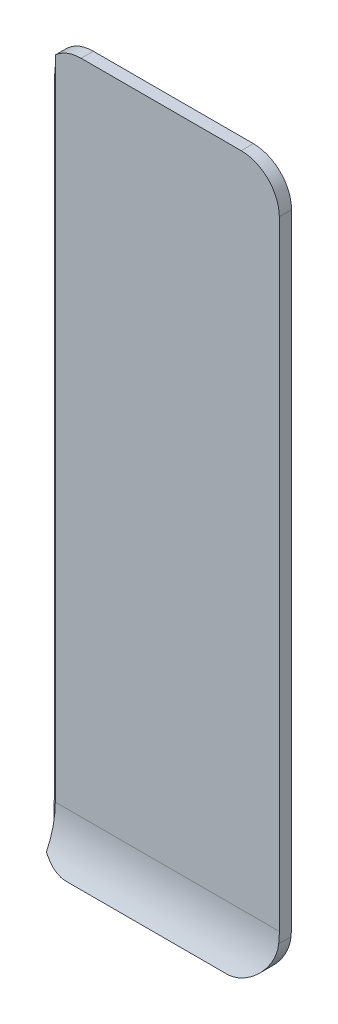
SolidWorks part; units mm, degrees
ref_plane "Front Plane" through (0, 0, 0) normal (0, 0, 1) x (1, 0, 0)
ref_plane "Top Plane" through (0, 0, 0) normal (0, 1, 0) x (1, 0, 0)
ref_plane "Right Plane" through (0, 0, 0) normal (1, 0, 0) x (0, 0, -1)
sketch "Sketch1" plane through (0, 0, 0) normal (0, 0, 1) x (1, 0, 0)
  line L1 (100, 0) -> (519, 0)
  line L2 (0, 100) -> (0, 1748)
  line L3 (100, 1848) -> (519, 1848)
  line L4 (619, 100) -> (619, 1748)
  arc A0 (100, 0) -> (0, 100) centre (100, 100) cw
  arc A1 (519, 0) -> (619, 100) centre (519, 100) ccw
  arc A2 (519, 1848) -> (619, 1748) centre (519, 1748) cw
  arc A3 (0, 1748) -> (100, 1848) centre (100, 1748) cw
  point P8 (0, 0)
  point P11 (619, 0)
  point P14 (619, 1848)
  dimension "D3" = 100
  dimension "D1" = 1848
  dimension "D2" = 619
extrude "Boss-Extrude1" add sketch "Sketch1" along normal blind 70
sketch "Sketch2" plane through (0, 0, 0) normal (-1, 0, 0) x (0, 0, 1)
  line L1 (70, 1848) -> (0, 1848) construction
  line L2 (32, 1848) -> (32, 127.4469)
  line L3 (70, 0) -> (32.6985, 0)
  line L4 (0, 1748) -> (0, 100) construction
  line L6 (70, 0) -> (0, 0) construction
  line L7 (0, 127.4469) -> (0, 0)
  line L8 (0, 0) -> (32.6985, 0)
  line L9 (70, 0) -> (70, 1848)
  line L10 (70, 1848) -> (32, 1848)
  arc A0 (32, 127.4469) -> (70, 0) centre (264.72, 127.4469) ccw
  arc A1 (32.6985, 0) -> (0, 127.4469) centre (264.72, 127.4469) cw
  line M8 (0, 100) -> (70, 100)
  line M9 (70, 100) -> (70, 1748)
  line M10 (70, 1748) -> (0, 1748)
  dimension "D2" = 264.72
  dimension "D1" = 32
extrude "Cut-Extrude1" cut sketch "Sketch2" against normal through all contours L8 A1 L7 M8 | A0 L9 M8 | L2 A0 M8 M9 M10
sketch "Sketch4" plane through (0, 0, 0) normal (-1, 0, 0) x (0, 0, 1)
  line L0 (32, 1848) -> (0, 1848) construction
  line L1 (1, 1848) -> (32, 1848)
  line L2 (1, 1848) -> (1, 127.4469)
  line L4 (32, 1848) -> (32, 127.4469)
  line L5 (70, 0) -> (32.6985, 0) construction
  line L6 (33.8401, 0) -> (70, 0)
  line L7 (0, 1848) -> (0, 1748) construction
  arc A0 (1, 127.4469) -> (33.8401, 0) centre (264.72, 127.4469) ccw
  arc A1 (1.4267, 100) -> (32.6985, 0) centre (264.72, 127.4469) ccw construction
  arc A2 (32, 127.4469) -> (70, 0) centre (264.72, 127.4469) ccw
  dimension "D1" = 1
extrude "Cut-Extrude2" cut sketch "Sketch4" against normal blind 32.5
